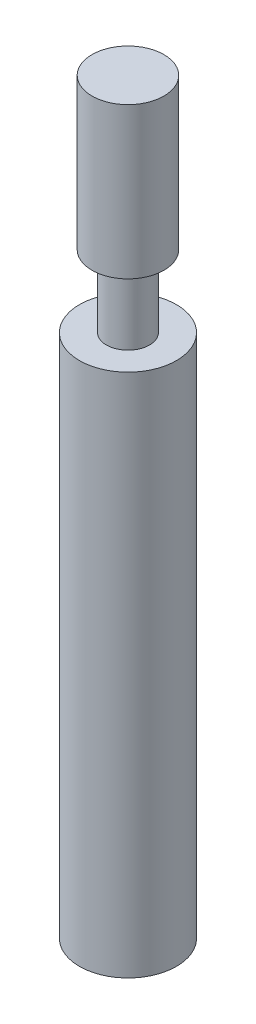
SolidWorks part; units mm, degrees
ref_plane "Front" through (0, 0, 0) normal (0, 0, 1) x (1, 0, 0)
ref_plane "Top" through (0, 0, 0) normal (0, 1, 0) x (1, 0, 0)
ref_plane "Right" through (0, 0, 0) normal (1, 0, 0) x (0, 0, -1)
sketch "Sketch1" plane through (0, 0, 0) normal (0, 1, 0) x (1, 0, 0)
  circle A0 centre (0, 0) radius 3.375
  dimension "D1" = 6.75
extrude "Boss-Extrude1" add sketch "Sketch1" along normal blind 41.5
sketch "Sketch2" plane through (0, 41.5, 0) normal (0, 1, 0) x (1, 0, 0)
  circle A0 centre (0, 0) radius 2.5
  dimension "D1" = 5
extrude "Boss-Extrude2" add sketch "Sketch2" along normal blind 10.5
sketch "Sketch3" plane through (0, 41.5, 0) normal (0, 1, 0) x (1, 0, 0)
  circle A0 centre (0, 0) radius 1.5
  circle A1 centre (0, 0) radius 3.375
  circle A2 centre (0, 0) radius 3.375
  dimension "D2" = 3
  dimension "D1" = 0
extrude "Cut-Extrude1" cut sketch "Sketch3" against normal blind 5
